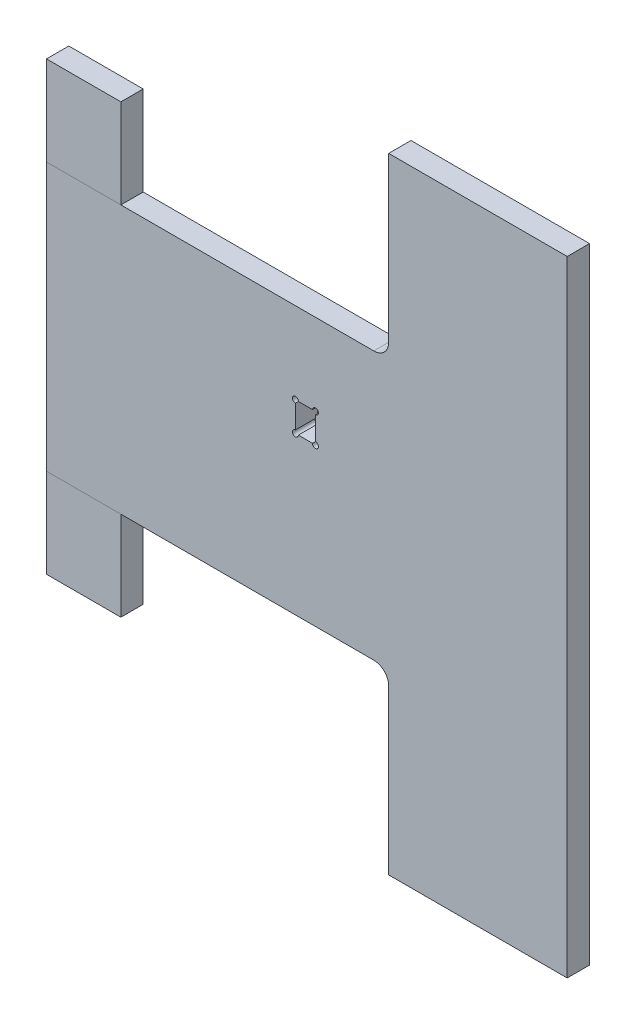
SolidWorks part; units mm, degrees
material "铝材"
ref_plane "前基準面" through (0, 0, 0) normal (0, 0, 1) x (1, 0, 0)
ref_plane "上基準面" through (0, 0, 0) normal (0, 1, 0) x (1, 0, 0)
ref_plane "右基準面" through (0, 0, 0) normal (1, 0, 0) x (0, 0, -1)
sketch "草图1" plane through (0, 0, 0) normal (0, 0, 1) x (1, 0, 0)
  line L1 (0, 0) -> (400, 0)
  line L2 (0, 0) -> (0, 180)
  line L3 (0, 180) -> (400, 180)
  line L4 (400, 0) -> (400, 180)
  dimension "D1" = 180
  dimension "D2" = 400
extrude "凸台-拉伸1" add sketch "草图1" along normal blind 15
sketch "草图3" plane through (0, 0, 15) normal (0, 0, 1) x (1, 0, 0)
  line L1 (169.3, 123.25) -> (178.8, 123.25)
  line L2 (169.3, 123.25) -> (169.3, 107.65)
  line L3 (169.3, 107.65) -> (178.8, 107.65)
  line L4 (178.8, 123.25) -> (178.8, 107.65)
  dimension "D1" = 9.5
extrude "切除-拉伸2" cut sketch "草图3" against normal through all
sketch "草图4" plane through (0, 0, 15) normal (0, 0, 1) x (1, 0, 0)
  line L8 (167.3, 105.65) -> (180.8, 105.65)
  line L9 (180.8, 105.65) -> (180.8, 125.25)
  line L10 (180.8, 125.25) -> (167.3, 125.25)
  line L11 (167.3, 125.25) -> (167.3, 105.65)
  line L12 (167.3, 105.65) -> (180.8, 105.65)
  line L13 (180.8, 105.65) -> (180.8, 125.25)
  line L14 (180.8, 125.25) -> (167.3, 125.25)
  line L15 (167.3, 125.25) -> (167.3, 105.65)
  dimension "D1" = 2
extrude "切除-拉伸3" cut sketch "草图4" against normal through all
sketch "草图5" plane through (0, 0, 15) normal (0, 0, 1) x (1, 0, 0)
  circle A0 centre (167.3, 125.25) radius 2
  circle A1 centre (167.3, 105.65) radius 2
  circle A2 centre (180.8, 105.65) radius 2
  circle A3 centre (180.8, 125.25) radius 2
  dimension "D1" = 4
extrude "切除-拉伸4" cut sketch "草图5" against normal through all
sketch "草图6" plane through (0, 180, 0) normal (0, 1, 0) x (1, 0, 0)
  line L0 (400, 0) -> (0, 0) construction
  line L1 (330, 0) -> (230, 0)
  line L2 (330, 0) -> (330, -15)
  line L3 (330, -15) -> (230, -15)
  line L4 (230, 0) -> (230, -15)
  line L5 (400, -15) -> (0, -15) construction
  line L6 (0, -15) -> (0, 0) construction
  dimension "D1" = 100
  dimension "D2" = 230
extrude "凸台-拉伸2" add sketch "草图6" along normal blind 120
sketch "草图7" plane through (0, 0, 0) normal (0, -1, 0) x (1, 0, 0)
  line L0 (0, 15) -> (400, 15) construction
  line L1 (330, 15) -> (230, 15)
  line L2 (330, 15) -> (330, 0)
  line L3 (330, 0) -> (230, 0)
  line L4 (230, 15) -> (230, 0)
  line L5 (0, 0) -> (400, 0) construction
  line L6 (0, 15) -> (0, 0) construction
  dimension "D1" = 230
  dimension "D2" = 100
extrude "凸台-拉伸3" add sketch "草图7" along normal blind 120
fillet "圆角1" radius 10 2 edges
sketch "草图8" plane through (0, 0, 15) normal (0, 0, 1) x (1, 0, 0)
  line L0 (330, 0) -> (400, 0) construction
  line L1 (400, 180) -> (350, 180)
  line L2 (400, 180) -> (400, 0)
  line L3 (400, 0) -> (350, 0)
  line L4 (350, 180) -> (350, 0)
  line L5 (330, 300) -> (330, 180) construction
  dimension "D1" = 20
extrude "切除-拉伸5" cut sketch "草图8" against normal blind 120
fillet "圆角2" radius 10 2 edges
sketch "草图9" plane through (0, 180, 0) normal (0, 1, 0) x (1, 0, 0)
  line L0 (220, 0) -> (0, 0) construction
  line L1 (220, -15) -> (0, -15) construction
  line L4 (0, -15) -> (220, -15)
  line L5 (220, -15) -> (220, 0)
  line L6 (220, 0) -> (0, 0)
  line L7 (0, 0) -> (0, -15)
  line L8 (0, -15) -> (50, -15)
  line L9 (50, -15) -> (50, 0)
  line L10 (50, 0) -> (0, 0)
  line L11 (0, 0) -> (0, -15)
  dimension "D2" = 50
  dimension "D1" = 0
extrude "凸台-拉伸4" add sketch "草图9" along normal blind 60 separate body
sketch "草图10" plane through (0, 0, 0) normal (0, -1, 0) x (1, 0, 0)
  line L0 (0, 0) -> (220, 0) construction
  line L1 (0, 15) -> (220, 15) construction
  line L4 (0, 0) -> (220, 0)
  line L5 (220, 0) -> (220, 15)
  line L6 (220, 15) -> (0, 15)
  line L7 (0, 15) -> (0, 0)
  line L8 (0, 0) -> (50, 0)
  line L9 (50, 0) -> (50, 15)
  line L10 (50, 15) -> (0, 15)
  line L11 (0, 15) -> (0, 0)
  dimension "D2" = 50
  dimension "D1" = 0
extrude "凸台-拉伸5" add sketch "草图10" along normal blind 60 separate body
sketch "草图11" plane through (0, 0, 15) normal (0, 0, 1) x (1, 0, 0)
  line L1 (350, 0) -> (330, 0)
  line L2 (350, 0) -> (350, -120)
  line L3 (350, -120) -> (330, -120)
  line L4 (330, 0) -> (330, -120)
  line L5 (350, 180) -> (330, 180)
  line L6 (350, 180) -> (350, 300)
  line L7 (350, 300) -> (330, 300)
  line L8 (330, 180) -> (330, 300)
extrude "凸台-拉伸6" add sketch "草图11" against normal up to surface (15 mm away) up to face at (253.75, 90, 0)
